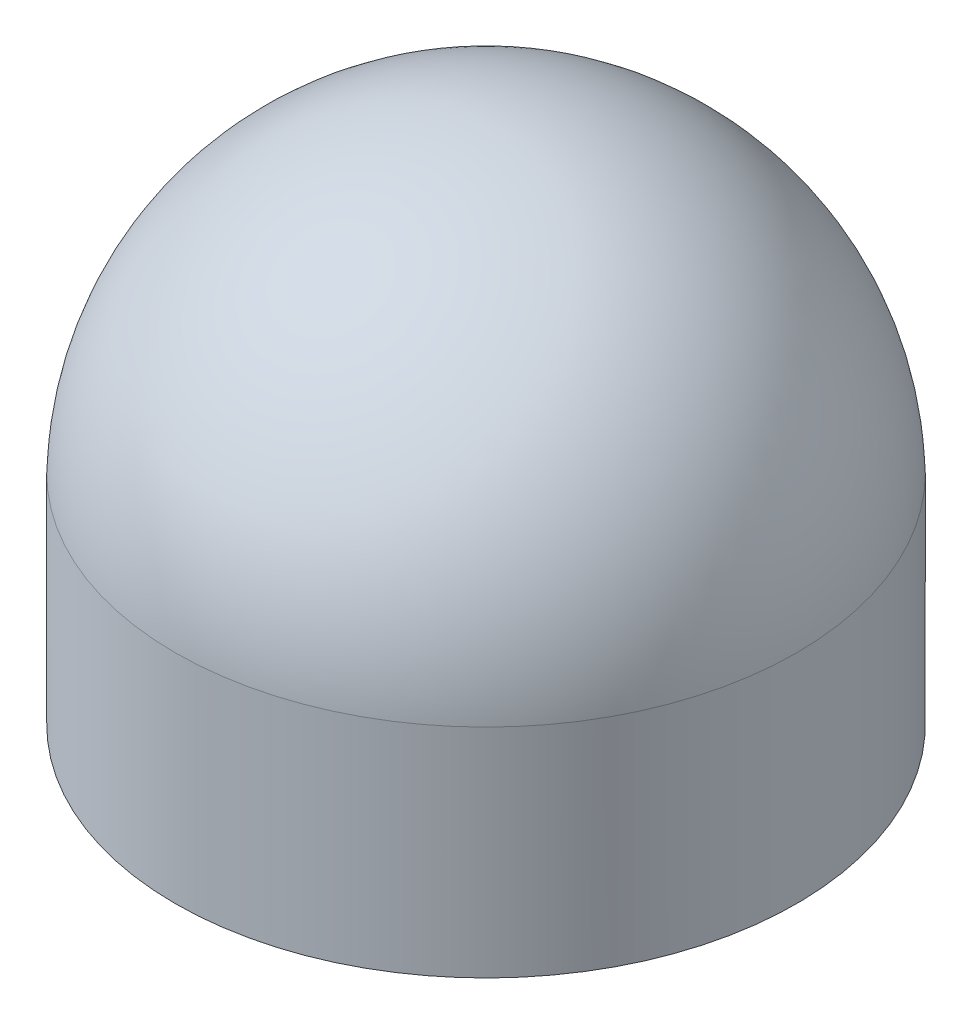
SolidWorks part; units mm, degrees
ref_plane "Front Plane" through (0, 0, 0) normal (0, 0, 1) x (1, 0, 0)
ref_plane "Top Plane" through (0, 0, 0) normal (0, 1, 0) x (1, 0, 0)
ref_plane "Right Plane" through (0, 0, 0) normal (1, 0, 0) x (0, 0, -1)
sketch "Sketch1" plane through (0, 0, 0) normal (1, 0, 0) x (0, 0, -1)
  line L0 (2.6, 0) -> (2.6, 2.5)
  line L1 (0, 0) -> (2.6, 0) construction
  line L3 (0, 0) -> (0, 5) construction
  line L5 (3.6, 0) -> (3.6, 2.518)
  line L6 (0, 6) -> (0, 5)
  line L7 (2.6, 0) -> (3.6, 0)
  arc A2 (0, 5) -> (2.6, 2.5) centre (0, 2.398) cw
  arc A3 (0, 6) -> (3.6, 2.518) centre (0, 2.398) cw
  dimension "D1" = 5
  dimension "D2" = 2.6
  dimension "D3" = 2.5
  dimension "D4" = 1
revolve "Revolve3" add sketch "Sketch1" angle 360 about L6
equation "\"D3@Sketch1\"=\"D1@Sketch1\"/2"
